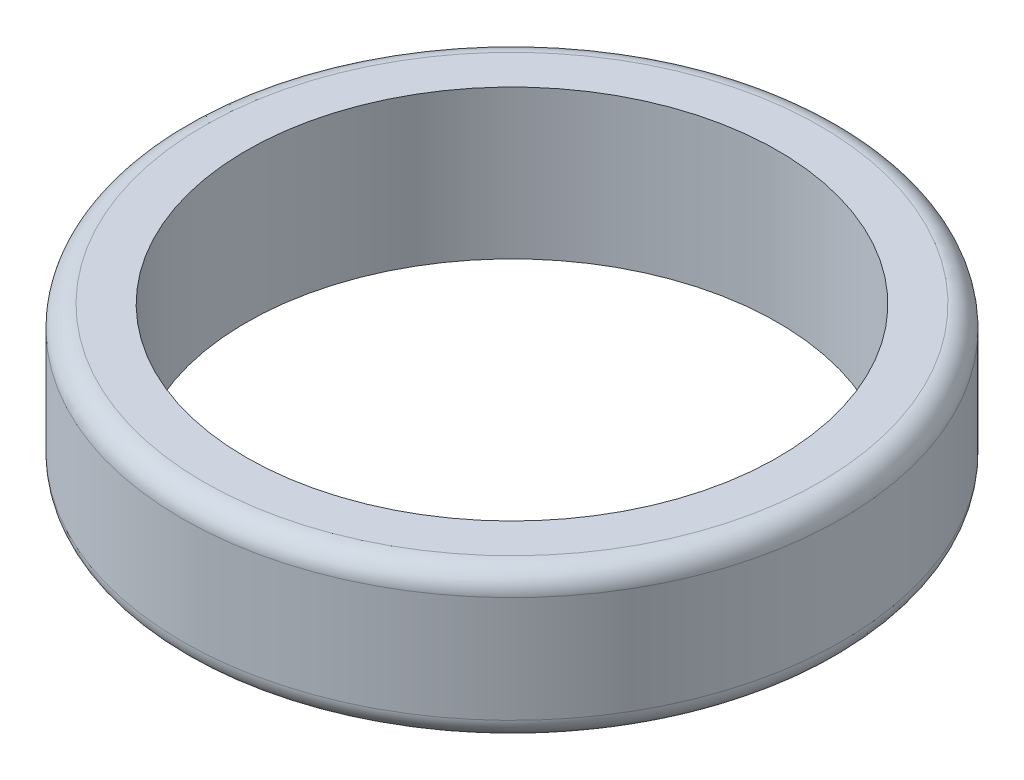
SolidWorks part; units mm, degrees
ref_plane "Front Plane" through (0, 0, 0) normal (0, 0, 1) x (1, 0, 0)
ref_plane "Top Plane" through (0, 0, 0) normal (0, 1, 0) x (1, 0, 0)
ref_plane "Right Plane" through (0, 0, 0) normal (1, 0, 0) x (0, 0, -1)
sketch "Sketch1" plane through (0, 0, 0) normal (0, 1, 0) x (1, 0, 0)
  circle A0 centre (0, 0) radius 12.5
  circle A1 centre (0, 0) radius 15.5
  dimension "D1" = 25
  dimension "D2" = 31
extrude "Boss-Extrude1" add sketch "Sketch1" along normal blind 7
fillet "Fillet1" radius 1 2 edges at (0, 0, 15.5) (0, 7, 15.5)
